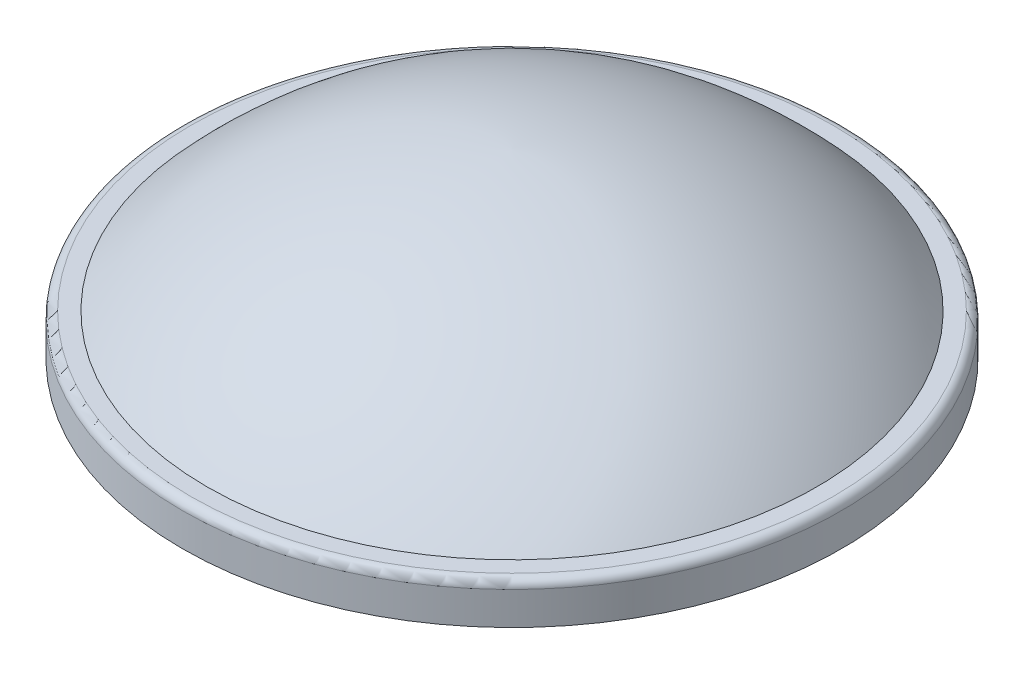
SolidWorks part; units mm, degrees
ref_plane "Face" through (0, 0, 0) normal (0, 0, 1) x (1, 0, 0)
ref_plane "Dessus" through (0, 0, 0) normal (0, 1, 0) x (1, 0, 0)
ref_plane "Droite" through (0, 0, 0) normal (1, 0, 0) x (0, 0, -1)
sketch "Esquisse1" plane through (0, 0, 0) normal (0, 0, 1) x (1, 0, 0)
  line L0 (0, 0) -> (-4, 0)
  line L1 (-4, 0) -> (-4, 0.5)
  line L2 (-4, 0.5) -> (-3.7, 0.5)
  line L3 (0, 0) -> (0, 2.1982)
  line L4 (0, -1.3692) -> (0, 4.2328) construction
  arc A0 (-3.7, 0.5) -> (0, 2.1982) centre (0.1675, -3.0465) cw
revolve "Révolution1" add sketch "Esquisse1" angle 360 about L4
fillet "Congé1" radius 0.1 1 edges at (0, 0.5, -4)
